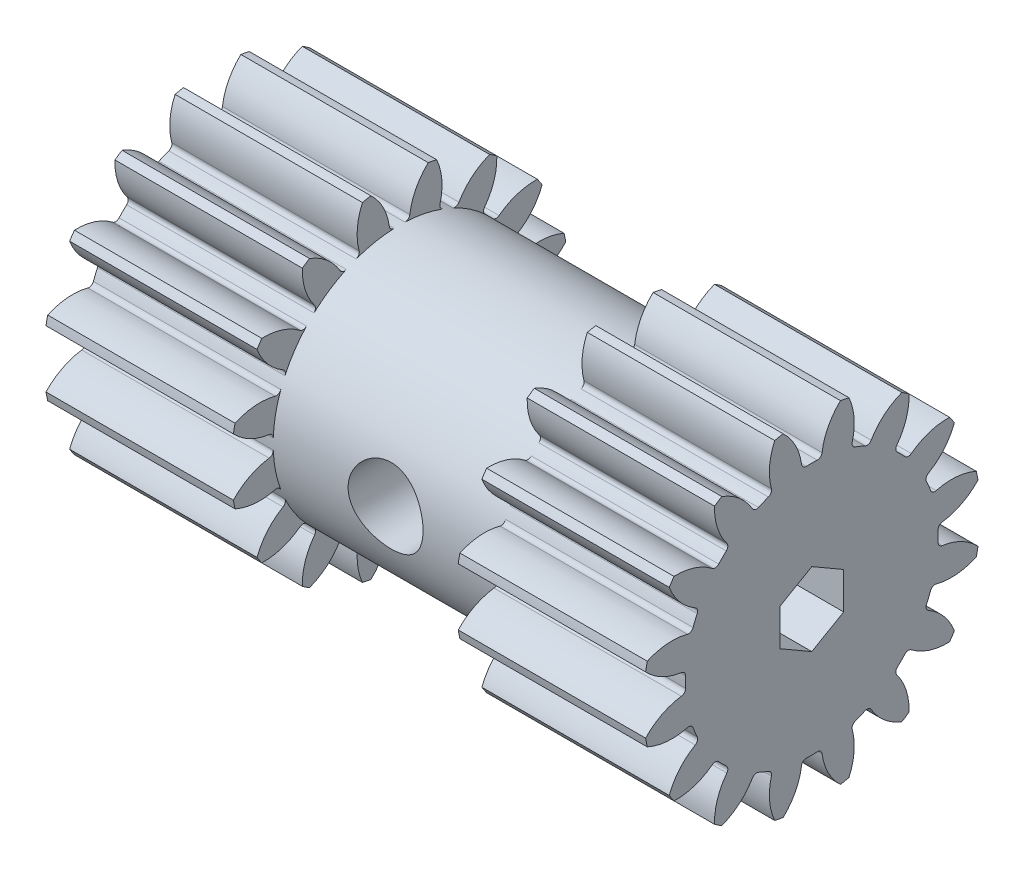
SolidWorks part; units mm, degrees
other "GearB2" parameters "Num_teeth"=16
material "Nylon 101"
ref_plane "Plane1" through (0, 0, 0) normal (0, 0, 1) x (1, 0, 0)
ref_plane "Plane2" through (0, 0, 0) normal (0, 1, 0) x (1, 0, 0)
ref_plane "Plane3" through (0, 0, 0) normal (1, 0, 0) x (0, 0, -1)
sketch "BasProSke" plane through (0, 0, 0) normal (0, 1, 0) x (1, 0, 0)
  line L0 (-10, 0) -> (60, 0) construction
  line L1 (0, 0) -> (0, 4.5)
  line L2 (0, 0) -> (16, 0)
  line L3 (16, 0) -> (16, 4.5)
  line L4 (16, 4.5) -> (0, 4.5)
  dimension "Diameter" = 9
  dimension "Thickness" = 16
revolve "Base-Revolve" add sketch "BasProSke" angle 360 about L0
sketch "TooCutSke" plane through (0, 0, 0) normal (1, 0, 0) x (0, 0, -1)
  line L1 (0, 0) -> (0, 107) construction
  line L2 (0, 0) -> (-0.4253, 3.9773) construction
  line L3 (0, 0) -> (-1.5544, 7.8146) construction
  line L4 (-0.4253, 3.9773) -> (-0.7772, 3.9073) construction
  arc A0 (0.2619, 3.3638) -> (-0.2619, 3.3638) centre (0, 0) ccw
  arc A1 (0.7886, 4.4562) -> (-0.7886, 4.4562) centre (0, 0) ccw
  circle A2 centre (0, 0) radius 4 construction
  circle A3 centre (0, 0) radius 3.7588 construction
  arc A4 (-0.2619, 3.3638) -> (-0.7886, 4.4562) centre (-1.8589, 3.2669) ccw
  arc A5 (0.7886, 4.4562) -> (0.2619, 3.3638) centre (1.8589, 3.2669) ccw
  dimension "Root_dia" = 6.748
  dimension "Overcut_dia" = 9.0508
  dimension "Pitch_dia" = 8
  dimension "Base_dia" = 7.5175
  dimension "Flank_rad" = 1.6
  dimension "Half_ang" = 11.25
  dimension "Half_CT" = 0.3588
extrude "ToothCut" cut sketch "TooCutSke" along normal through all
fillet "RootFillets" radius 0.126 2 edges at (8, 3.3638, -0.2619) (8, 3.3638, 0.2619)
pattern_circular "TeethCuts" count 16 over 360 about axis through (0, 0, 0) along (1, 0, 0) of "ToothCut", "RootFillets"
sketch "ShaftHoleSke" plane through (16, 0, 0) normal (1, 0, 0) x (0, 0, -1)
  line L2 (0, 0.9815) -> (-0.85, 0.4907)
  line L3 (-0.85, 0.4907) -> (-0.85, -0.4907)
  line L4 (-0.85, -0.4907) -> (0, -0.9815)
  line L5 (0, -0.9815) -> (0.85, -0.4907)
  line L6 (0.85, -0.4907) -> (0.85, 0.4907)
  line L7 (0.85, 0.4907) -> (0, 0.9815)
  circle A1 centre (0, 0) radius 0.85 construction
  dimension "D1" = 1.7
extrude "ShaftHole" cut sketch "ShaftHoleSke" against normal through all
sketch "ScrewHoleSke" plane through (0, 0, -0.85) normal (0, 0, 1) x (1, 0, 0)
  line L0 (0, 0) -> (16, 0) construction
  line L1 (0, 0.143) -> (0, -0.143) construction
  line L2 (16, -0.143) -> (16, 0.143) construction
  circle A0 centre (8, 0) radius 1
  point P11 (8, 0)
  dimension "D1" = 2
extrude "ScrewHole" cut sketch "ScrewHoleSke" against normal through all both and the other way through all
ref_plane "Plane" through (8, 0, 0) normal (1, 0, 0) x (0, 0, -1)
sketch "CutSke" plane through (8, 0, 0) normal (1, 0, 0) x (0, 0, -1)
  circle A0 centre (0, 0) radius 3.374
  circle A1 centre (0, 0) radius 4.5
  arc A2 (3.1691, 1.1579) -> (3.0597, 1.4221) centre (0, 0) ccw construction
  arc A3 (4.4345, 0.765) -> (4.3897, 0.9903) centre (0, 0) ccw construction
extrude "Cut" cut sketch "CutSke" against normal mid plane 6
equation "\"OAL@HoldingSke\" = \"Thickness@HoldingSke\""
equation "\"MHD@HoldingSke\" = (\"Num_teeth@HoldingSke\" + 2) / \"Pitch@HoldingSke\" - 2 * (\"Addendum_fac@HoldingSke\" + \"Dedendum_fac@HoldingSke\")  / \"Pitch@HoldingSke\" - \"Dedendum_add@HoldingSke\" * 2"
equation "\"MBD@HoldingSke\" = (\"Num_teeth@HoldingSke\" + 2) / \"Pitch@HoldingSke\" - 2 * (\"Addendum_fac@HoldingSke\" + \"Dedendum_fac@HoldingSke\")  / \"Pitch@HoldingSke\" - \"Dedendum_add@HoldingSke\" * 2 - 0.002 * 25.4"
equation "\"MHD@HoldingSke\" = ((sgn( \"MHD@HoldingSke\" - \"Hub_dia@HoldingSke\" )-1)*( \"MHD@HoldingSke\" - \"Hub_dia@HoldingSke\" ))/-2+ \"Hub_dia@HoldingSke\""
equation "\"Num_teeth@TeethCuts\" = int( \"Show_teeth@HoldingSke\" ) + 1"
equation "\"Num_teeth@TeethCuts\" = ((sgn( \"Num_teeth@TeethCuts\" - \"Num_teeth@HoldingSke\" )-1)*( \"Num_teeth@TeethCuts\" - \"Num_teeth@HoldingSke\" ))/-2+ \"Num_teeth@HoldingSke\""
